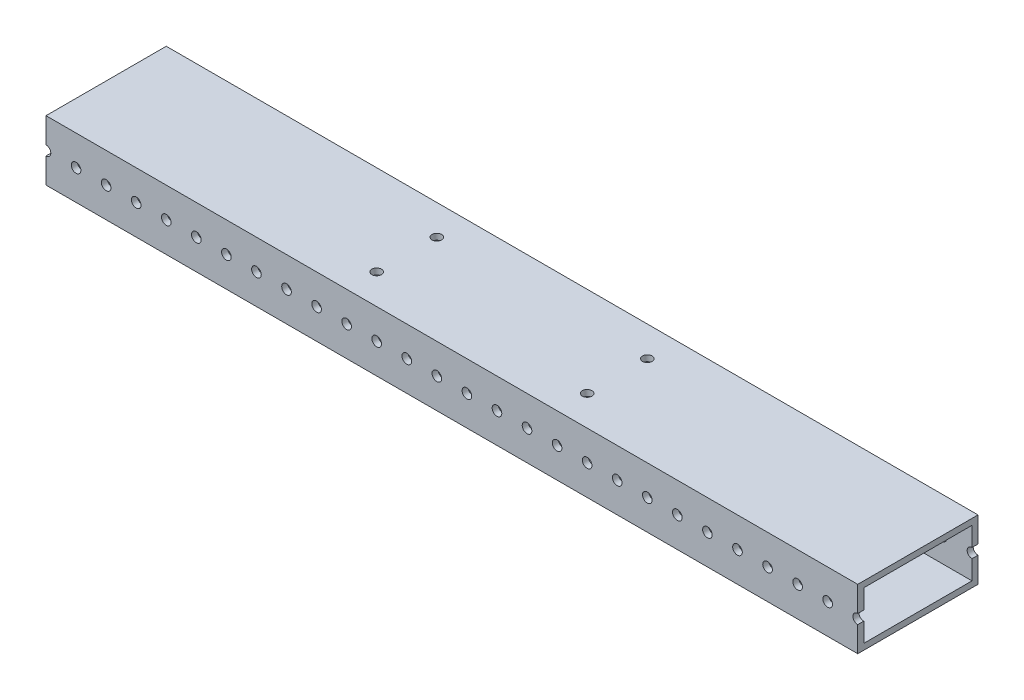
SolidWorks part; units mm, degrees
ref_plane "Front Plane" through (0, 0, 0) normal (0, 0, 1) x (1, 0, 0)
ref_plane "Top Plane" through (0, 0, 0) normal (0, 1, 0) x (1, 0, 0)
ref_plane "Right Plane" through (0, 0, 0) normal (1, 0, 0) x (0, 0, -1)
sketch "Sketch1" plane through (0, 0, 0) normal (1, 0, 0) x (0, 0, -1)
  line L0 (-22.86, 10.16) -> (22.86, 10.16)
  line L1 (-25.4, -12.7) -> (25.4, -12.7)
  line L2 (-25.4, -12.7) -> (-25.4, 12.7)
  line L3 (-25.4, 12.7) -> (25.4, 12.7)
  line L4 (25.4, -12.7) -> (25.4, 12.7)
  line L5 (-25.4, -12.7) -> (25.4, 12.7) construction
  line L6 (-25.4, 12.7) -> (25.4, -12.7) construction
  line L7 (22.86, -10.16) -> (22.86, 10.16)
  line L8 (-22.86, -10.16) -> (22.86, -10.16)
  line L9 (-22.86, -10.16) -> (-22.86, 10.16)
  point P0 (0, 0)
  dimension "D1" = 50.8
  dimension "D2" = 25.4
  dimension "D3" = 2.54
extrude "Boss-Extrude1" add sketch "Sketch1" along normal mid plane 342.9
sketch "Sketch2" plane through (0, 0, 25.4) normal (0, 0, 1) x (1, 0, 0)
  line L0 (-171.45, 12.7) -> (-171.45, -12.7) construction
  circle A0 centre (-171.45, 0) radius 2.032
  circle A1 centre (-158.75, 0) radius 2.032
  circle A2 centre (-146.05, 0) radius 2.032
  circle A3 centre (-133.35, 0) radius 2.032
  circle A4 centre (-120.65, 0) radius 2.032
  circle A5 centre (-107.95, 0) radius 2.032
  circle A6 centre (-95.25, 0) radius 2.032
  circle A7 centre (-82.55, 0) radius 2.032
  circle A8 centre (-69.85, 0) radius 2.032
  circle A9 centre (-57.15, 0) radius 2.032
  circle A10 centre (-44.45, 0) radius 2.032
  circle A11 centre (-31.75, 0) radius 2.032
  circle A12 centre (-19.05, 0) radius 2.032
  circle A13 centre (-6.35, 0) radius 2.032
  circle A14 centre (6.35, 0) radius 2.032
  circle A15 centre (19.05, 0) radius 2.032
  circle A16 centre (31.75, 0) radius 2.032
  circle A17 centre (44.45, 0) radius 2.032
  circle A18 centre (57.15, 0) radius 2.032
  circle A19 centre (69.85, 0) radius 2.032
  circle A20 centre (82.55, 0) radius 2.032
  circle A21 centre (95.25, 0) radius 2.032
  circle A22 centre (107.95, 0) radius 2.032
  circle A23 centre (120.65, 0) radius 2.032
  circle A24 centre (133.35, 0) radius 2.032
  circle A25 centre (146.05, 0) radius 2.032
  circle A26 centre (158.75, 0) radius 2.032
  circle A27 centre (171.45, 0) radius 2.032
  circle A28 centre (184.15, 0) radius 2.032
  circle A29 centre (196.85, 0) radius 2.032
  circle A30 centre (209.55, 0) radius 2.032
  circle A31 centre (222.25, 0) radius 2.032
  circle A32 centre (234.95, 0) radius 2.032
  circle A33 centre (247.65, 0) radius 2.032
  circle A34 centre (260.35, 0) radius 2.032
  circle A35 centre (273.05, 0) radius 2.032
  circle A36 centre (285.75, 0) radius 2.032
  circle A37 centre (298.45, 0) radius 2.032
  circle A38 centre (311.15, 0) radius 2.032
  circle A39 centre (323.85, 0) radius 2.032
  dimension "D1" = 4.064
  dimension "D2" = 40
extrude "Cut-Extrude1" cut sketch "Sketch2" against normal through all
sketch "Sketch3" plane through (0, -12.7, 0) normal (0, -1, 0) x (1, 0, 0)
  line L0 (0, 25.4) -> (0, -25.4) construction
  line L1 (171.45, 25.4) -> (-171.45, 25.4) construction
  line L2 (171.45, -25.4) -> (-171.45, -25.4) construction
  line L3 (0, 0) -> (24.4913, 0) construction
  line L4 (171.45, 25.4) -> (171.45, -25.4) construction
  circle A0 centre (44.45, 12.7) radius 2.032
  circle A1 centre (44.45, -12.7) radius 2.032
  circle A2 centre (-44.45, -12.7) radius 2.032
  circle A3 centre (-44.45, 12.7) radius 2.032
  dimension "D1" = 4.064
  dimension "D2" = 12.7
  dimension "D3" = 127
extrude "Cut-Extrude2" cut sketch "Sketch3" against normal through all
